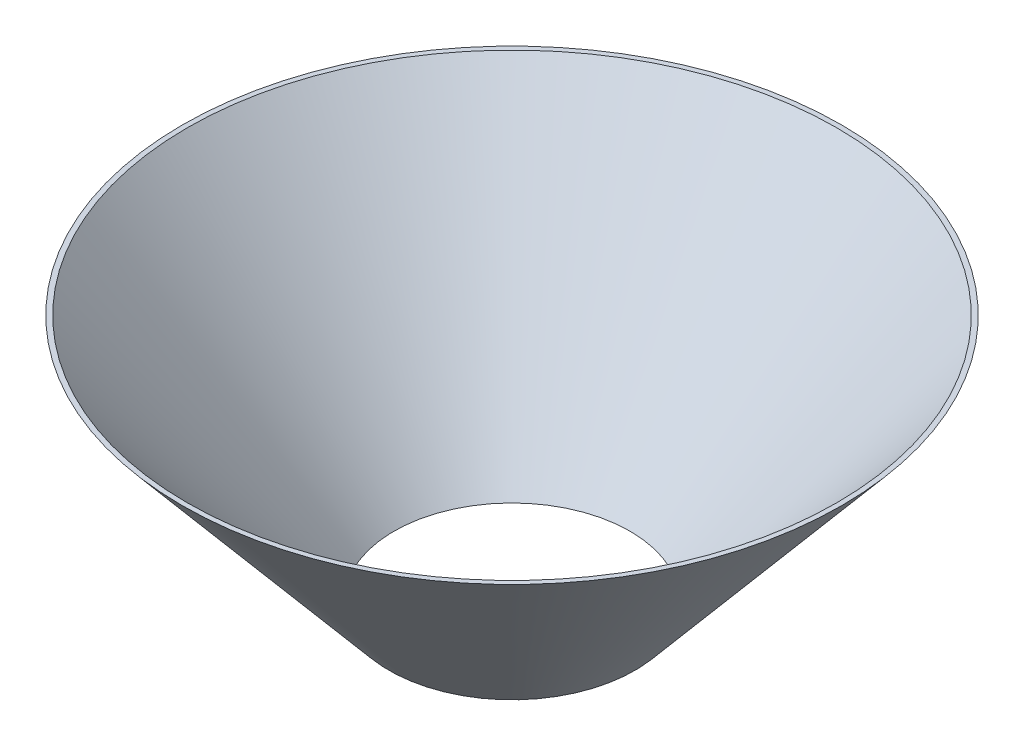
SolidWorks part; units mm, degrees
ref_plane "前视基准面" through (0, 0, 0) normal (0, 0, 1) x (1, 0, 0)
ref_plane "上视基准面" through (0, 0, 0) normal (0, 1, 0) x (1, 0, 0)
ref_plane "右视基准面" through (0, 0, 0) normal (1, 0, 0) x (0, 0, -1)
sketch "草图1" plane through (0, 0, 0) normal (0, 0, 1) x (1, 0, 0)
  line L0 (-50, 91.8992) -> (84, 91.8992)
  line L1 (84, 91.8992) -> (0, -8.1008)
  line L2 (0, -8.1008) -> (-50, -8.1008)
  line L3 (-50, -8.1008) -> (-50, 91.8992)
  dimension "D1" = 50
  dimension "D2" = 100
  dimension "D3" = 134
revolve "旋转1" add sketch "草图1" angle 360 about L3
sketch "草图2" plane through (0, 0, 0) normal (0, 0, 1) x (1, 0, 0)
  line L0 (-50, 91.8992) -> (82, 91.8992)
  line L1 (-50, 91.8992) -> (84, 91.8992) construction
  line L2 (82, 91.8992) -> (-2, -8.1008)
  line L3 (0, -8.1008) -> (-50, -8.1008) construction
  line L4 (-2, -8.1008) -> (-50, -8.1008)
  line L5 (-50, -8.1008) -> (-50, 91.8992)
  dimension "D1" = 100
  dimension "D2" = 132
  dimension "D3" = 48
revolve "切除-旋转2" cut sketch "草图2" angle 360 about L5
